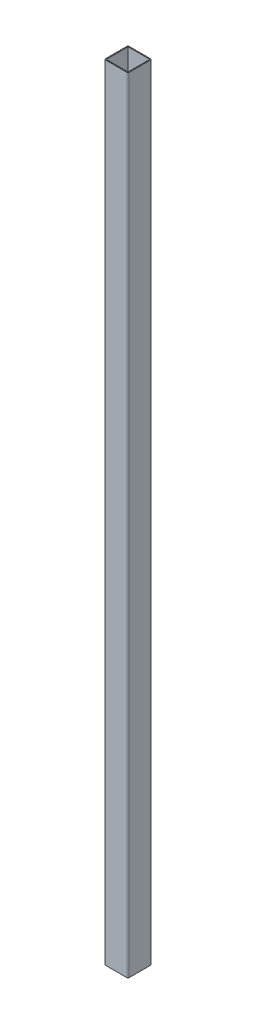
SolidWorks part; units mm, degrees
material "Простая углеродистая сталь"
ref_plane "Спереди" through (0, 0, 0) normal (0, 0, 1) x (1, 0, 0)
ref_plane "Сверху" through (0, 0, 0) normal (0, 1, 0) x (1, 0, 0)
ref_plane "Справа" through (0, 0, 0) normal (1, 0, 0) x (0, 0, -1)
sketch "Эскиз1" plane through (0, 0, 0) normal (0, 0, 1) x (1, 0, 0)
  line L0 (0, 0) -> (0, -5307)
  dimension "D1" = 5307
other "Квадратная труба гост 8639-82 150 X 150 X 7.0(1)"
ref_plane "Плоскость1" through (0, 0, 0) normal (0, -1, 0) x (1, 0, 0)
sketch "Sketch1" plane through (0, 0, 0) normal (0, -1, 0) x (1, 0, 0)
  line L0 (-73.999, -74) -> (73.999, -74)
  line L1 (-74, -73.999) -> (-74, 73.999)
  line L2 (73.999, 74) -> (-73.999, 74)
  line L3 (74, 73.999) -> (74, -73.999)
  line L4 (-73.999, -80) -> (73.999, -80)
  line L5 (-80, -73.999) -> (-80, 73.999)
  line L6 (73.999, 80) -> (-73.999, 80)
  line L7 (80, 73.999) -> (80, -73.999)
  arc A0 (80, 73.999) -> (73.999, 80) centre (73.999, 73.999) ccw
  arc A1 (73.999, -80) -> (80, -73.999) centre (73.999, -73.999) ccw
  arc A2 (-80, -73.999) -> (-73.999, -80) centre (-73.999, -73.999) ccw
  arc A3 (-73.999, 80) -> (-80, 73.999) centre (-73.999, 73.999) ccw
  arc A4 (-73.999, 74) -> (-74, 73.999) centre (-73.999, 73.999) ccw
  arc A5 (74, 73.999) -> (73.999, 74) centre (73.999, 73.999) ccw
  arc A6 (73.999, -74) -> (74, -73.999) centre (73.999, -73.999) ccw
  arc A7 (-74, -73.999) -> (-73.999, -74) centre (-73.999, -73.999) ccw
  point P0 (-80, 0)
  point P1 (80, 0)
  point P2 (0, 80)
  point P3 (0, -80)
  point P4 (0, 0)
  point P5 (-80, -80)
  point P6 (80, -80)
  point P7 (80, 80)
  point P8 (-80, 80)
  point P33 (0, 0)
  dimension "D1" = 6.001
  dimension "Thickness" = 6
  dimension "V_leg" = 160
sketch "Эскиз3" plane through (0, 0, 80) normal (0, 0, 1) x (1, 0, 0)
  line L0 (-80, 0) -> (80, -20)
  line L1 (80, -5307) -> (80, 0) construction
  line L2 (80, -20) -> (80, 0)
  line L3 (80, 0) -> (-80, 0)
  dimension "D1" = 20
extrude "Вырез-Вытянуть1" [suppressed] cut sketch "Эскиз3" against normal up to vertex
equation "\"D1@Sketch1\" = \"Thickness@Sketch1\"+0.001"
